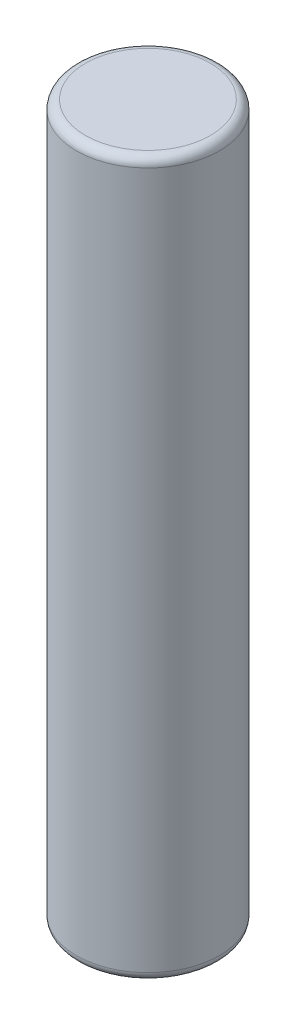
SolidWorks part; units mm, degrees
ref_plane "Front Plane" through (0, 0, 0) normal (0, 0, 1) x (1, 0, 0)
ref_plane "Top Plane" through (0, 0, 0) normal (0, 1, 0) x (1, 0, 0)
ref_plane "Right Plane" through (0, 0, 0) normal (1, 0, 0) x (0, 0, -1)
sketch "Sketch1" plane through (0, 0, 0) normal (0, 1, 0) x (1, 0, 0)
  circle A0 centre (0, 0.7182) radius 4
  dimension "D1" = 8
extrude "Boss-Extrude1" add sketch "Sketch1" along normal blind 40
fillet "Fillet1" radius 0.5 2 edges at (0, 0, 3.2818) (0, 40, 3.2818)
